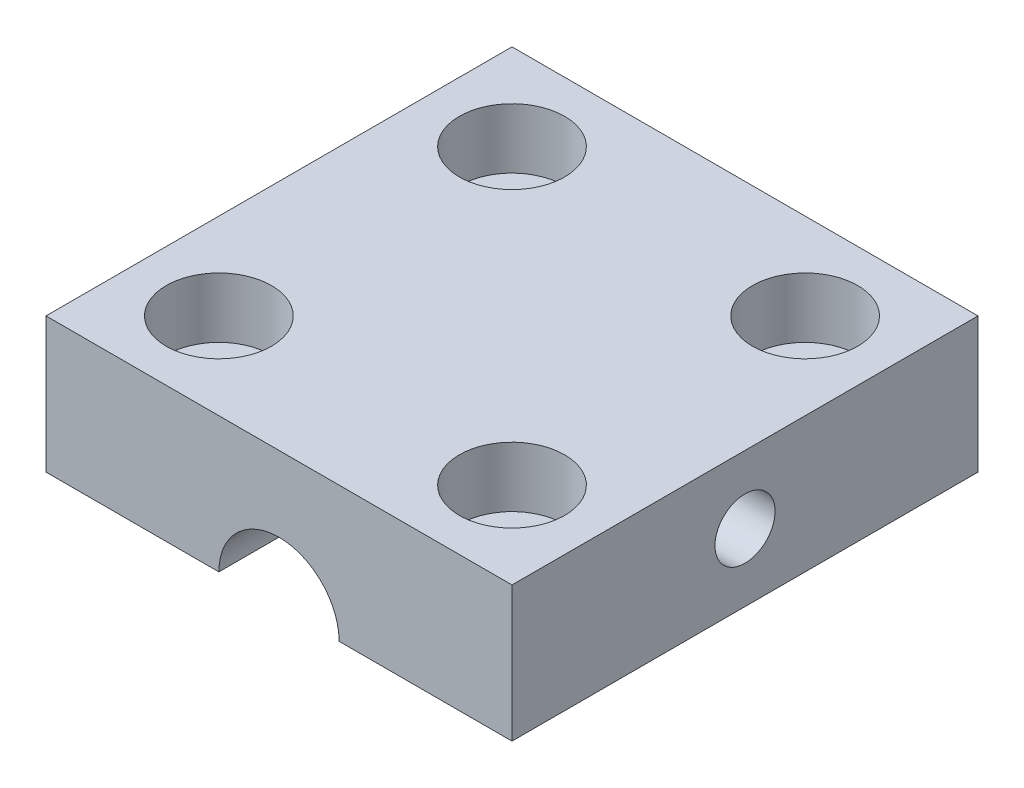
SolidWorks part; units mm, degrees
ref_plane "Přední rovina" through (0, 0, 0) normal (0, 0, 1) x (1, 0, 0)
ref_plane "Horní rovina" through (0, 0, 0) normal (0, 1, 0) x (1, 0, 0)
ref_plane "Pravá rovina" through (0, 0, 0) normal (1, 0, 0) x (0, 0, -1)
sketch "Skica2" plane through (0, 0, 0) normal (0, 0, 1) x (1, 0, 0)
  line L0 (0, 0) -> (15.5, 0) construction
  line L1 (0, 0) -> (0, 4.5) construction
  line L2 (15.5, -4.5) -> (15.5, 4.5)
  line L3 (15.5, 4.5) -> (-15.5, 4.5)
  line L4 (-15.5, -4.5) -> (-15.5, 4.5)
  line L5 (15.5, -4.5) -> (4, -4.5)
  line L6 (-4, -4.5) -> (-15.5, -4.5)
  arc A0 (4, -4.5) -> (-4, -4.5) centre (0, -4.5) ccw
  point P9 (-15.5, 0)
  point P10 (0, 0)
  dimension "D3" = 4
  dimension "D1" = 31
  dimension "D2" = 9
  dimension "D4" = 4
  dimension "D5" = 4
extrude "Přidat vysunutím1" add sketch "Skica2" along normal blind 31
sketch "Skica3" plane through (0, 4.5, 0) normal (0, 1, 0) x (1, 0, 0)
  line L0 (15.5, -15.5) -> (0, -15.5) construction
  line L1 (15.5, -31) -> (15.5, 0) construction
  line L2 (0, -15.5) -> (0, 0) construction
  line L3 (15.5, -5.75) -> (9.75, -5.75) construction
  line L4 (15.5, 0) -> (-15.5, 0) construction
  circle A0 centre (9.75, -5.75) radius 3.5
  circle A1 centre (9.75, -25.25) radius 3.5
  circle A2 centre (-9.75, -5.75) radius 3.5
  circle A3 centre (-9.75, -25.25) radius 3.5
  dimension "D3" = 7
  dimension "D1" = 5.75
  dimension "D2" = 5.75
extrude "Odebrat vysunutím1" cut sketch "Skica3" against normal blind 4
sketch "Skica4" plane through (0, 4.5, 0) normal (0, 1, 0) x (1, 0, 0)
  circle A0 centre (9.75, -5.75) radius 2
  circle A1 centre (-9.75, -5.75) radius 2
  circle A2 centre (-9.75, -25.25) radius 2
  circle A3 centre (9.75, -25.25) radius 2
  dimension "D1" = 4
  dimension "D2" = 4
  dimension "D3" = 4
  dimension "D4" = 4
extrude "Odebrat vysunutím2" cut sketch "Skica4" against normal through all
sketch "Skica5" plane through (15.5, 0, 0) normal (1, 0, 0) x (0, 0, -1)
  line L0 (-15.5, -4.5) -> (-15.5, 0) construction
  line L1 (-31, -4.5) -> (0, -4.5) construction
  circle A0 centre (-15.5, 0) radius 2
  dimension "D2" = 4
  dimension "D1" = 4.5
extrude "Odebrat vysunutím3" cut sketch "Skica5" against normal blind 10
